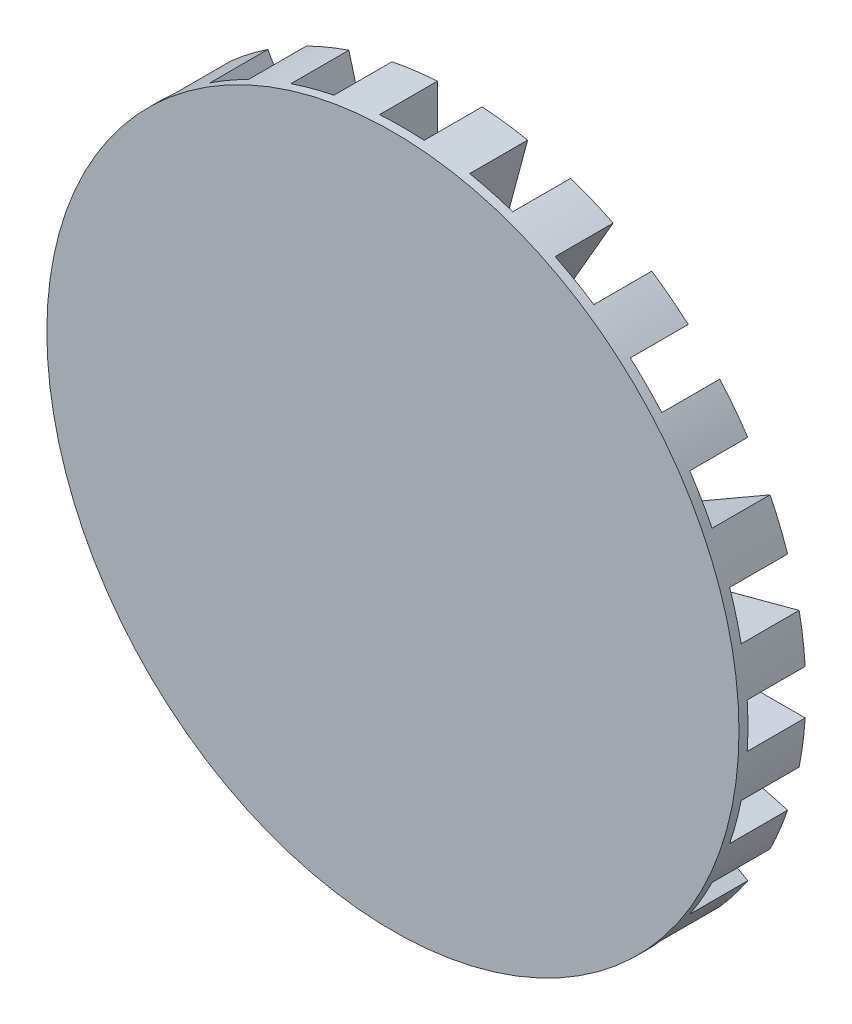
SolidWorks part; units mm, degrees
material "PUR"
ref_plane "Front Plane" through (0, 0, 0) normal (0, 0, 1) x (1, 0, 0)
ref_plane "Top Plane" through (0, 0, 0) normal (0, 1, 0) x (1, 0, 0)
ref_plane "Right Plane" through (0, 0, 0) normal (1, 0, 0) x (0, 0, -1)
sketch "Sketch1" plane through (0, 0, 0) normal (0, 0, 1) x (1, 0, 0)
  circle A0 centre (0, 0) radius 77.6077
  circle A2 centre (0, 0) radius 89.6077 construction
  circle A3 centre (0, 0) radius 89.6077 construction
  dimension "D1" = 12
extrude "Boss-Extrude1" add sketch "Sketch1" along normal blind 2 from offset 13
sketch "Sketch3" plane through (0, 0, 15) normal (0, 0, 1) x (1, 0, 0)
  line L0 (0, 0) -> (0, -77.6077) construction
  line L1 (0, 0) -> (-20.0863, -74.9633) construction
  line L2 (-5, -77.4465) -> (-5, -37.9788)
  line L3 (-5, -37.9788) -> (-15.215, -76.1016)
  line L4 (-5, -57.7126) -> (0, -57.7126) construction
  line L5 (-10.1075, -57.0402) -> (-14.9371, -55.7461) construction
  circle A0 centre (0, 0) radius 77.6077 construction
  arc A1 (-5, -77.4465) -> (-15.215, -76.1016) centre (0, 0) cw
  dimension "D1" = 10
  dimension "D2" = 15
extrude "Boss-Extrude2" add sketch "Sketch3" against normal up to surface (15 mm away)
pattern_circular "CirPattern1" count 24 over 360 about axis through (0, 0, 0) along (0, 0, 1) of "Boss-Extrude2"
